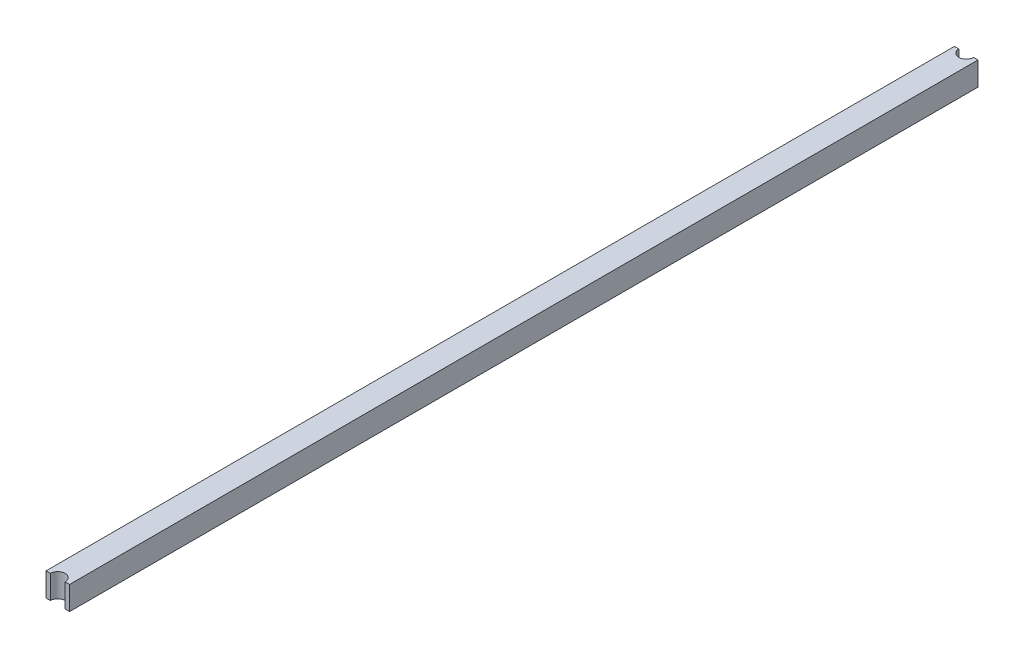
SolidWorks part; units mm, degrees
material "Plain Carbon Steel"
ref_plane "Front Plane" through (0, 0, 0) normal (0, 0, 1) x (1, 0, 0)
ref_plane "Top Plane" through (0, 0, 0) normal (0, 1, 0) x (1, 0, 0)
ref_plane "Right Plane" through (0, 0, 0) normal (1, 0, 0) x (0, 0, -1)
sketch "Sketch2" plane through (0, 0, 0) normal (0, 0, 1) x (1, 0, 0)
  line L1 (-31.1, 31.1) -> (0, 31.1)
  line L2 (-31.1, 31.1) -> (-31.1, 0)
  line L3 (-31.1, 0) -> (0, 0)
  line L4 (0, 31.1) -> (0, 0)
extrude "Boss-Extrude1" add sketch "Sketch2" along normal blind 1200
sketch "Sketch4" plane through (0, 31.1, 0) normal (0, 1, 0) x (1, 0, 0)
  line L0 (0, -1200) -> (-31.1, -1200) construction
  line L1 (0, 0) -> (-31.1, 0) construction
  circle A0 centre (-15.55, -1200) radius 9.755
  circle A1 centre (-15.55, 0) radius 9.755
extrude "Cut-Extrude1" cut sketch "Sketch4" against normal blind 31.1
